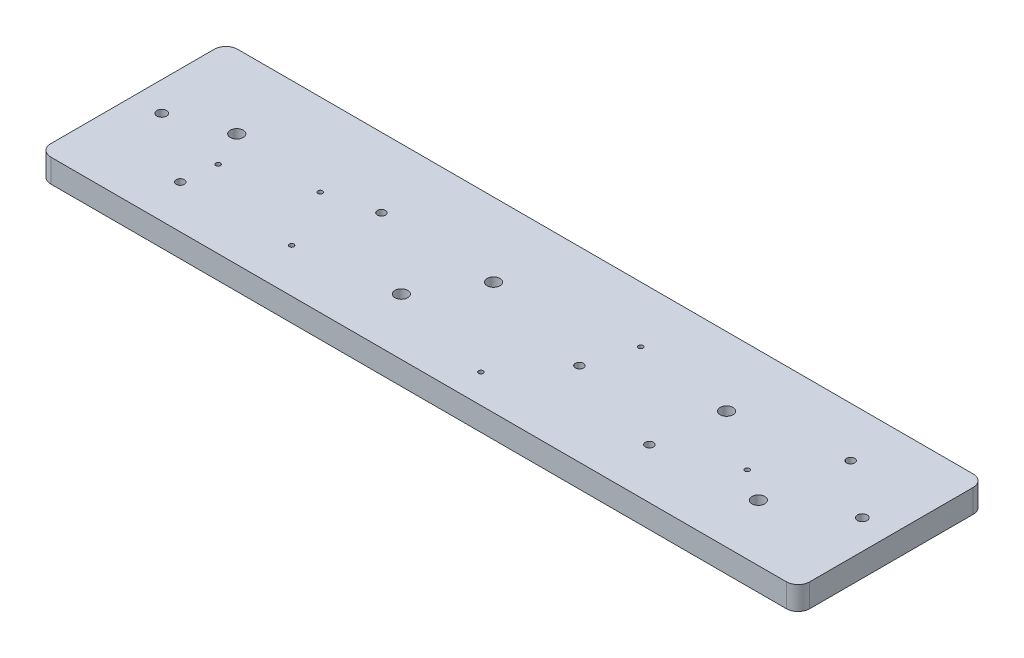
SolidWorks part; units mm, degrees
material "1060 Alloy"
ref_plane "Front Plane" through (0, 0, 0) normal (0, 0, 1) x (1, 0, 0)
ref_plane "Top Plane" through (0, 0, 0) normal (0, 1, 0) x (1, 0, 0)
ref_plane "Right Plane" through (0, 0, 0) normal (1, 0, 0) x (0, 0, -1)
sketch "Sketch1" plane through (0, 0, 0) normal (0, 1, 0) x (1, 0, 0)
  line L1 (0, 0) -> (650, 0)
  line L2 (0, 0) -> (0, 160)
  line L3 (0, 160) -> (650, 160)
  line L4 (650, 0) -> (650, 160)
  dimension "D1" = 160
  dimension "D2" = 650
extrude "Boss-Extrude1" add sketch "Sketch1" along normal blind 20 contours L3 L4 L1 L2
fillet "Fillet1" radius 10 4 edges at (0, 10, -160) (0, 10, 0) (650, 10, -160) (650, 10, 0)
sketch "Sketch4" plane through (0, 20, 0) normal (0, 1, 0) x (1, 0, 0)
  point P0 (72.3526, 96.8991)
  point P2 (261.6679, 48.5488)
  point P4 (487.7567, 100.9851)
  point P6 (567.4326, 48.5488)
  point P8 (292.3125, 96.8991)
hole_wizard "Ø11.0 (11) Diameter Hole1" positions "Sketch4" profile "Sketch3" hole size "Ø11.0" standard "DIN" end condition through all
sketch "Sketch3" plane through (72.3526, 20, -96.8991) normal (1, 0, 0) x (0, 0, 1)
  line L0 (0, 0) -> (0, 20)
  line L1 (0, 20) -> (5.5, 20)
  line L2 (5.5, 20) -> (5.5, 0)
  line L5 (5.5, 0) -> (0, 0)
  line L11 (0, -6.35) -> (0, 107.95) construction
  dimension "Thru Hole Dia." = 11
  dimension "Thru Hole Depth" = 20
sketch "Sketch7" plane through (0, 20, 0) normal (0, 1, 0) x (1, 0, 0)
  point P0 (192.8879, 100.3041)
  point P2 (83.9294, 36.972)
  point P4 (391.0561, 71.7025)
  point P6 (577.6474, 117.3288)
  point P8 (479.5848, 43.1009)
hole_wizard "Ø7.0 (7) Diameter Hole1" positions "Sketch7" profile "Sketch6" hole size "Ø7.0" standard "DIN" end condition through all
sketch "Sketch6" plane through (192.8879, 20, -100.3041) normal (1, 0, 0) x (0, 0, 1)
  line L0 (0, 0) -> (0, 20)
  line L1 (0, 20) -> (3.5, 20)
  line L2 (3.5, 20) -> (3.5, 0)
  line L5 (3.5, 0) -> (0, 0)
  line L11 (0, -6.35) -> (0, 107.95) construction
  dimension "Thru Hole Dia." = 7
  dimension "Thru Hole Depth" = 20
sketch "Sketch10" plane through (0, 20, 0) normal (0, 1, 0) x (1, 0, 0)
  point P0 (178.5871, 37.653)
  point P2 (151.3475, 89.4082)
  point P4 (353.6016, 24.7141)
  point P6 (403.3139, 111.8809)
  point P10 (540.1929, 66.2546)
  point P18 (87.0078, 66.2546)
hole_wizard "Ø4.0 (4) Diameter Hole1" positions "Sketch10" profile "Sketch9" hole size "Ø4.0" standard "DIN" end condition through all
sketch "Sketch9" plane through (178.5871, 20, -37.653) normal (1, 0, 0) x (0, 0, 1)
  line L0 (0, 0) -> (0, 20)
  line L1 (0, 20) -> (2, 20)
  line L2 (2, 20) -> (2, 0)
  line L5 (2, 0) -> (0, 0)
  line L11 (0, -6.35) -> (0, 107.95) construction
  dimension "Thru Hole Dia." = 4
  dimension "Thru Hole Depth" = 20
other "DeleteFace3" [suppressed]
sketch "Sketch11" plane through (0, 20, 0) normal (0, 1, 0) x (1, 0, 0)
  line L0 (0, 80) -> (25, 80) construction
  line L1 (0, 10) -> (0, 150) construction
  line L3 (650, 80) -> (625, 80) construction
  line L4 (650, 10) -> (650, 150) construction
  line L6 (10, 0) -> (640, 0) construction
  line L7 (25, 160) -> (25, 0) construction
  line L8 (10, 160) -> (640, 160) construction
  line L10 (625, 160) -> (625, 0) construction
  point P9 (25, 80)
  point P17 (625, 80)
  dimension "D1" = 25
  dimension "D2" = 25
hole_wizard "M8 Clearance Hole1" positions "Sketch11" profile "Sketch12" hole size "M8" standard "DIN" end condition through all
sketch "Sketch12" plane through (625, 20, -80) normal (1, 0, 0) x (0, 0, 1)
  line L0 (0, 0) -> (0, 20)
  line L1 (0, 20) -> (4.2, 20)
  line L2 (4.2, 20) -> (4.2, 0)
  line L5 (4.2, 0) -> (0, 0)
  line L11 (0, -6.35) -> (0, 107.95) construction
  dimension "Thru Hole Dia." = 8.4
  dimension "Thru Hole Depth" = 20
